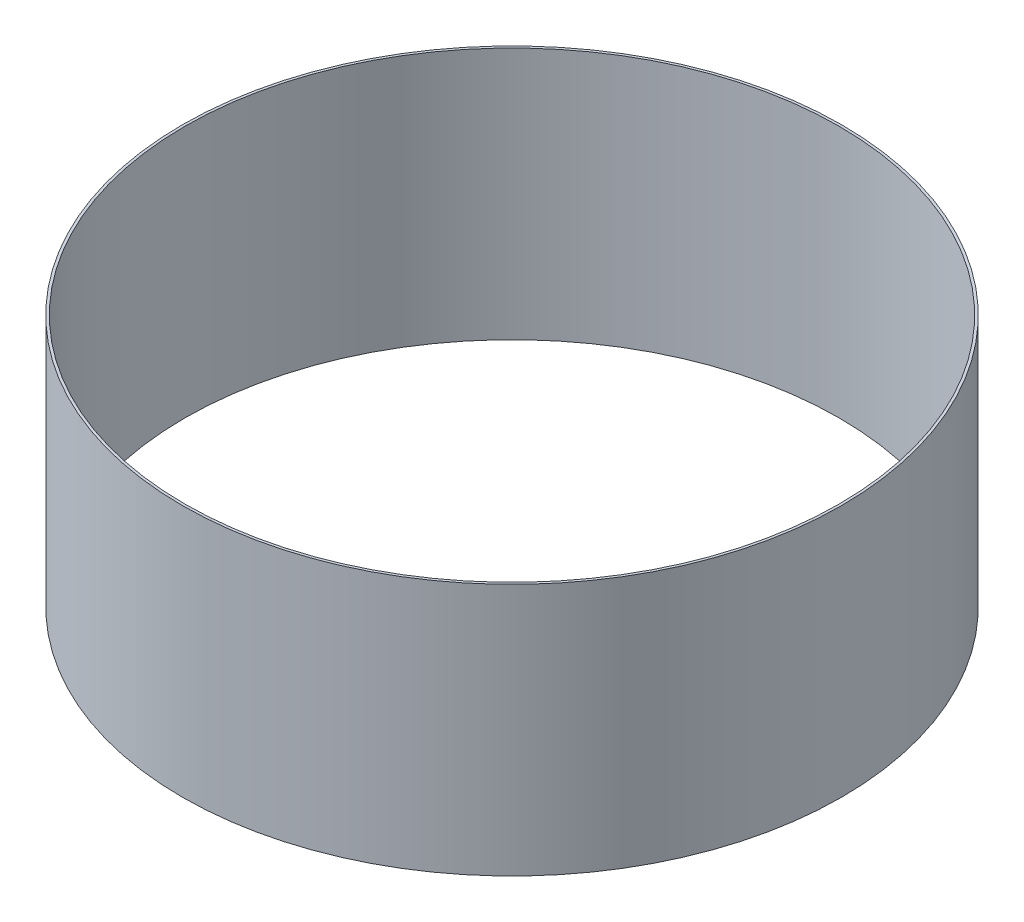
SolidWorks part; units mm, degrees
ref_plane "Plan de face" through (0, 0, 0) normal (0, 0, 1) x (1, 0, 0)
ref_plane "Plan de dessus" through (0, 0, 0) normal (0, 1, 0) x (1, 0, 0)
ref_plane "Plan de droite" through (0, 0, 0) normal (1, 0, 0) x (0, 0, -1)
sketch "Esquisse1" plane through (0, 0, 0) normal (0, 1, 0) x (1, 0, 0)
  circle A0 centre (0, 0) radius 32.625
  circle A1 centre (0, 0) radius 32.375
  dimension "D1" = 64.75
  dimension "D2" = 65.25
extrude "Extrusion1" add sketch "Esquisse1" along normal blind 25
